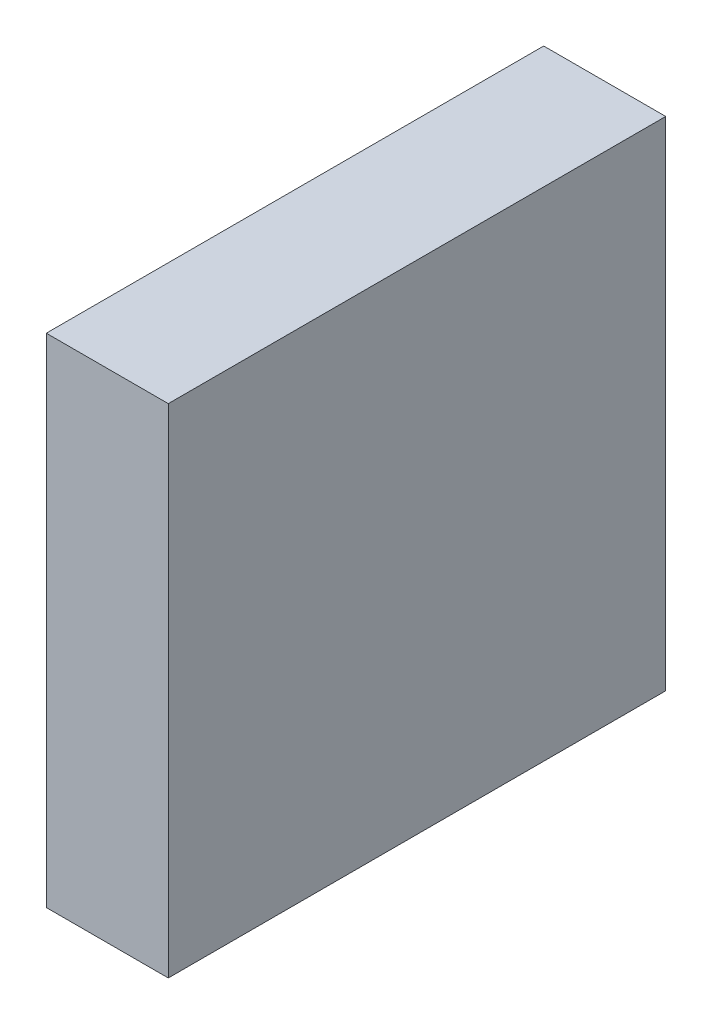
SolidWorks part; units mm, degrees
ref_plane "Front Plane" through (0, 0, 0) normal (0, 0, 1) x (1, 0, 0)
ref_plane "Top Plane" through (0, 0, 0) normal (0, 1, 0) x (1, 0, 0)
ref_plane "Right Plane" through (0, 0, 0) normal (1, 0, 0) x (0, 0, -1)
sketch "Sketch1" plane through (0, 0, 0) normal (1, 0, 0) x (0, 0, -1)
  line L1 (0, 0) -> (-53, 0)
  line L2 (0, 0) -> (0, -53)
  line L3 (0, -53) -> (-53, -53)
  line L4 (-53, 0) -> (-53, -53)
  dimension "D1" = 53
  dimension "D2" = 53
extrude "Boss-Extrude1" add sketch "Sketch1" along normal blind 13
